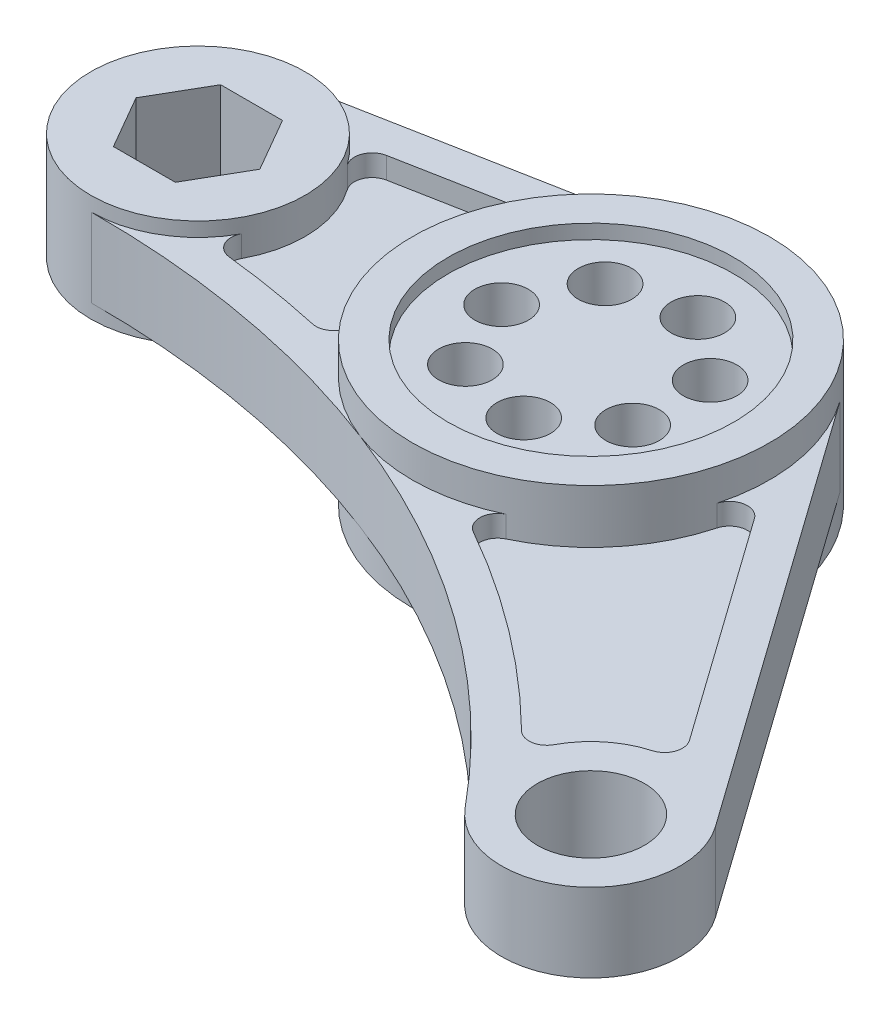
SolidWorks part; units mm, degrees
ref_plane "前视基准面" through (0, 0, 0) normal (0, 0, 1) x (1, 0, 0)
ref_plane "上视基准面" through (0, 0, 0) normal (0, 1, 0) x (1, 0, 0)
ref_plane "右视基准面" through (0, 0, 0) normal (1, 0, 0) x (0, 0, -1)
other "Configuration Table"
sketch "草图1" plane through (0, 0, 0) normal (0, 1, 0) x (1, 0, 0)
  line L0 (-37.7596, 0) -> (38.4857, 0) construction
  line L1 (0, -25) -> (0, 41.9349) construction
  line L2 (-110, -44.8395) -> (-110, 45.2025) construction
  line L3 (-92.6795, 0) -> (-101.3397, 15)
  line L4 (-101.3397, 15) -> (-118.6603, 15)
  line L5 (-118.6603, 15) -> (-127.3205, 0)
  line L6 (-127.3205, 0) -> (-118.6603, -15)
  line L7 (-118.6603, -15) -> (-101.3397, -15)
  line L8 (-101.3397, -15) -> (-92.6795, 0)
  line L9 (-110, 30) -> (-9.3304, 49.1217)
  line L10 (-110, -30) -> (-9.3304, -49.1217)
  circle A0 centre (0, 0) radius 25
  circle A1 centre (-110, 0) radius 15 construction
  circle A2 centre (-25, 0) radius 7.5
  circle A3 centre (-15.5872, 19.5458) radius 7.5
  circle A4 centre (5.563, 24.3732) radius 7.5
  circle A5 centre (22.5242, 10.8471) radius 7.5
  circle A6 centre (22.5242, -10.8471) radius 7.5
  circle A7 centre (5.563, -24.3732) radius 7.5
  circle A8 centre (-15.5872, -19.5458) radius 7.5
  circle A9 centre (-110, 0) radius 30
  circle A10 centre (0, 0) radius 50
  circle A11 centre (0, 0) radius 40
  point P32 (0, 0)
  dimension "D1" = 50
  dimension "D4" = 15
  dimension "D6" = 60
  dimension "D7" = 100
  dimension "D8" = 80
  dimension "D2" = 110
  dimension "D3" = 30
  dimension "D5" = 7
extrude "凸台-拉伸2" add sketch "草图1" along normal mid plane 40 contours A10 A11 | A11 A8 A0 A2 A3 A4 A5 A6 A7 | A8 A0 A7 A6 A5 A4 A3 A2
sketch "草图4" plane through (0, 20, 0) normal (0, 1, 0) x (1, 0, 0)
  circle A0 centre (0, 0) radius 40
  dimension "D1" = 80
extrude "切除-拉伸1" cut sketch "草图4" against normal blind 4
mirror "镜向1" about plane through (0, 0, 0) normal (0, 1, 0) of "切除-拉伸1"
sketch "草图6" plane through (0, 0, 0) normal (0, 1, 0) x (1, 0, 0)
  line L0 (0, 0) -> (-110, 0) construction
  line L2 (-92.6795, 0) -> (-101.3397, 15)
  line L3 (-101.3397, 15) -> (-118.6603, 15)
  line L4 (-118.6603, 15) -> (-127.3205, 0)
  line L5 (-127.3205, 0) -> (-118.6603, -15)
  line L6 (-118.6603, -15) -> (-101.3397, -15)
  line L7 (-101.3397, -15) -> (-92.6795, 0)
  circle A0 centre (-110, 0) radius 15 construction
  circle A1 centre (-110, 0) radius 30
  dimension "D3" = 60
  dimension "D1" = 110
  dimension "D2" = 30
extrude "凸台-拉伸5" add sketch "草图6" along normal mid plane 30 separate body
sketch "草图8" plane through (0, 0, 0) normal (0, 1, 0) x (1, 0, 0)
  line L0 (0, 0) -> (236.6107, 0) construction
  line L1 (0, 0) -> (106.066, -106.066) construction
  circle A0 centre (106.066, -106.066) radius 25
  circle A1 centre (106.066, -106.066) radius 15
  dimension "D3" = 50
  dimension "D4" = 30
  dimension "D1" = 45
  dimension "D2" = 150
extrude "凸台-拉伸6" add sketch "草图8" along normal mid plane 22 separate body contours A0 | A1
sketch "草图9" plane through (0, 0, 0) normal (0, 1, 0) x (1, 0, 0)
  line L0 (-110, 0) -> (-110, 88.084) construction
  line L1 (-110, 30) -> (-9.3304, 49.1217)
  line L2 (40.7534, 28.9683) -> (126.4427, -91.5819)
  circle A0 centre (106.066, -106.066) radius 25 construction
  circle A1 centre (0, 0) radius 50 construction
  circle A2 centre (-110, 0) radius 30 construction
  circle A3 centre (106.066, -106.066) radius 25
  circle A4 centre (0, 0) radius 50
  circle A5 centre (-110, 0) radius 30
  arc A6 (86.7742, -121.9665) -> (-109.8106, -29.9994) centre (-108.2153, -282.6783) ccw
extrude "凸台-拉伸7" add sketch "草图9" along normal mid plane 22 contours A6 A4 L1 A5 | A6 A3 L2 A4
sketch "草图10" plane through (0, 0, 0) normal (0, 1, 0) x (1, 0, 0)
  line L2 (-108.1339, 20.1757) -> (-7.4644, 39.2974)
  line L3 (-82.3262, 25.0777) -> (-49.1455, 31.3802)
  line L11 (32.6027, 23.1746) -> (118.292, -97.3755)
  line L12 (57.1831, -11.4058) -> (101.9051, -74.3219)
  circle A0 centre (0, 0) radius 50 construction
  circle A1 centre (-110, 0) radius 30 construction
  arc A2 (-43.8295, 24.0619) -> (-46.1216, -19.3081) centre (0, 0) ccw
  arc A3 (-83.5771, -14.2067) -> (-85.4799, 17.2847) centre (-110, 0) ccw
  arc A4 (21.4375, -45.1711) -> (48.2798, -13.0024) centre (0, 0) ccw
  arc A5 (-85.4799, 17.2847) -> (-82.3262, 25.0777) centre (-81.3932, 20.1655) cw
  arc A6 (-14.3008, -37.3562) -> (-109.8737, -19.9996) centre (-108.2153, -282.6783) ccw
  arc A7 (-51.8074, -26.1223) -> (-79.7157, -21.5449) centre (-108.2153, -282.6783) ccw
  arc A8 (-79.7157, -21.5449) -> (-83.5771, -14.2067) centre (-79.1733, -16.5745) cw
  arc A9 (-51.8074, -26.1223) -> (-46.1216, -19.3081) centre (-50.7337, -21.2389) ccw
  arc A10 (-43.8295, 24.0619) -> (-49.1455, 31.3802) centre (-48.2125, 26.4681) ccw
  arc A11 (99.2025, -82.0266) -> (101.9051, -74.3219) centre (97.8298, -77.2188) ccw
  arc A12 (84.0102, -94.2957) -> (76.0909, -95.5043) centre (79.599, -91.9416) cw
  arc A13 (21.1195, -54.0402) -> (21.4375, -45.1711) centre (23.5813, -49.6883) cw
  arc A14 (48.2798, -13.0024) -> (57.1831, -11.4058) centre (53.1078, -14.3026) cw
  circle A25 centre (106.066, -106.066) radius 25 construction
  arc A26 (94.4909, -115.6063) -> (-14.3008, -37.3562) centre (-108.2153, -282.6783) ccw
  arc A27 (76.0909, -95.5043) -> (21.1195, -54.0402) centre (-108.2153, -282.6783) ccw
  arc A28 (99.2025, -82.0266) -> (84.0102, -94.2957) centre (106.066, -106.066) ccw
  arc A29 (-43.8295, 24.0619) -> (-46.1216, -19.3081) centre (0, 0) ccw
  point P37 (0, 0)
  dimension "D3" = 5
  dimension "D4" = 5
  dimension "D5" = 5
  dimension "D8" = 5
  dimension "D1" = 10
  dimension "D2" = 10
  dimension "D6" = 10
  dimension "D7" = 10
extrude "切除-拉伸2" cut sketch "草图10" against normal blind 6 from surface at 11 contours A2 A10 L3 A5 A3 A8 A7 A9 | A28 A11 L12 A14 A4 A13 A27 A12 starting at face at (-63.1331, 11, -2.5091)
sketch "草图11" plane through (0, -11, 0) normal (0, -1, 0) x (1, 0, 0)
  line L0 (101.9051, 74.3219) -> (57.1831, 11.4058) construction
  line L1 (-49.1455, -31.3802) -> (-82.3262, -25.0777) construction
  line L2 (101.9051, 74.3219) -> (57.1831, 11.4058)
  line L3 (-49.1455, -31.3802) -> (-82.3262, -25.0777)
  arc A0 (21.1195, 54.0402) -> (76.0909, 95.5043) centre (-108.2153, 282.6783) ccw construction
  arc A1 (84.0102, 94.2957) -> (76.0909, 95.5043) centre (79.599, 91.9416) ccw construction
  arc A2 (84.0102, 94.2957) -> (99.2025, 82.0266) centre (106.066, 106.066) ccw construction
  arc A3 (101.9051, 74.3219) -> (99.2025, 82.0266) centre (97.8298, 77.2188) ccw construction
  arc A4 (48.2798, 13.0024) -> (57.1831, 11.4058) centre (53.1078, 14.3026) ccw construction
  arc A5 (48.2798, 13.0024) -> (21.4375, 45.1711) centre (0, 0) ccw construction
  arc A6 (21.1195, 54.0402) -> (21.4375, 45.1711) centre (23.5813, 49.6883) ccw construction
  arc A7 (-79.7157, 21.5449) -> (-83.5771, 14.2067) centre (-79.1733, 16.5745) ccw construction
  arc A8 (-79.7157, 21.5449) -> (-51.8074, 26.1223) centre (-108.2153, 282.6783) ccw construction
  arc A9 (-46.1216, 19.3081) -> (-51.8074, 26.1223) centre (-50.7337, 21.2389) ccw construction
  arc A10 (-46.1216, 19.3081) -> (-43.8295, -24.0619) centre (0, 0) ccw construction
  arc A11 (-49.1455, -31.3802) -> (-43.8295, -24.0619) centre (-48.2125, -26.4681) ccw construction
  arc A12 (-85.4799, -17.2847) -> (-82.3262, -25.0777) centre (-81.3932, -20.1655) ccw construction
  arc A13 (-85.4799, -17.2847) -> (-83.5771, 14.2067) centre (-110, 0) ccw construction
  arc A14 (21.1195, 54.0402) -> (76.0909, 95.5043) centre (-108.2153, 282.6783) ccw
  arc A15 (84.0102, 94.2957) -> (76.0909, 95.5043) centre (79.599, 91.9416) ccw
  arc A16 (84.0102, 94.2957) -> (99.2025, 82.0266) centre (106.066, 106.066) ccw
  arc A17 (101.9051, 74.3219) -> (99.2025, 82.0266) centre (97.8298, 77.2188) ccw
  arc A18 (48.2798, 13.0024) -> (57.1831, 11.4058) centre (53.1078, 14.3026) ccw
  arc A19 (48.2798, 13.0024) -> (21.4375, 45.1711) centre (0, 0) ccw
  arc A20 (21.1195, 54.0402) -> (21.4375, 45.1711) centre (23.5813, 49.6883) ccw
  arc A21 (-79.7157, 21.5449) -> (-83.5771, 14.2067) centre (-79.1733, 16.5745) ccw
  arc A22 (-79.7157, 21.5449) -> (-51.8074, 26.1223) centre (-108.2153, 282.6783) ccw
  arc A23 (-46.1216, 19.3081) -> (-51.8074, 26.1223) centre (-50.7337, 21.2389) ccw
  arc A24 (-46.1216, 19.3081) -> (-43.8295, -24.0619) centre (0, 0) ccw
  arc A25 (-49.1455, -31.3802) -> (-43.8295, -24.0619) centre (-48.2125, -26.4681) ccw
  arc A26 (-85.4799, -17.2847) -> (-82.3262, -25.0777) centre (-81.3932, -20.1655) ccw
  arc A27 (-85.4799, -17.2847) -> (-83.5771, 14.2067) centre (-110, 0) ccw
extrude "切除-拉伸3" cut sketch "草图11" against normal blind 6
